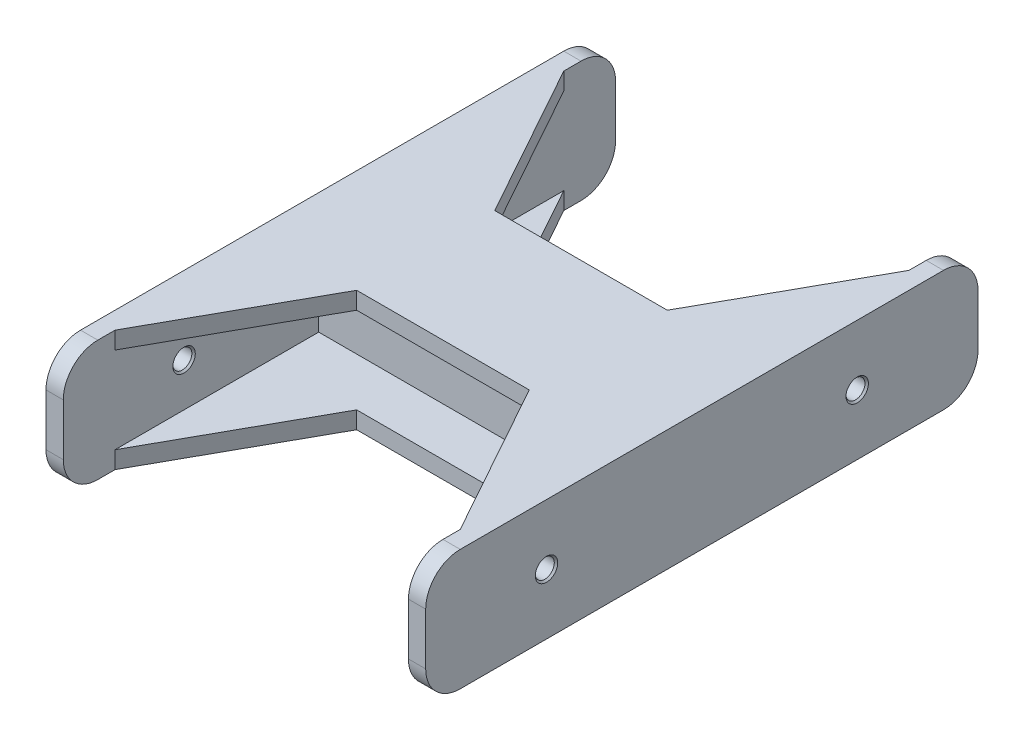
SolidWorks part; units mm, degrees
ref_plane "前视基准面" through (0, 0, 0) normal (0, 0, 1) x (1, 0, 0)
ref_plane "上视基准面" through (0, 0, 0) normal (0, 1, 0) x (1, 0, 0)
ref_plane "右视基准面" through (0, 0, 0) normal (1, 0, 0) x (0, 0, -1)
sketch "草图1" plane through (0, 0, 0) normal (1, 0, 0) x (0, 0, -1)
  line L1 (-80, 5) -> (80, 5)
  line L2 (-80, 5) -> (-80, -15)
  line L3 (-80, -15) -> (80, -15)
  line L4 (80, 5) -> (80, -15)
  dimension "D1" = 160
  dimension "D2" = 80
  dimension "D3" = 20
  dimension "D4" = 5
extrude "凸台-拉伸1" add sketch "草图1" along normal blind 5
sketch "草图3" plane through (5, 0, 0) normal (1, 0, 0) x (0, 0, -1)
  line L6 (-6, 5) -> (6, 5)
  line L7 (80, 5) -> (-80, 5) construction
  line L8 (6, 5) -> (6, -10)
  line L9 (6, -10) -> (20, -10)
  line L10 (20, -10) -> (20, -15)
  line L11 (-80, -15) -> (80, -15) construction
  line L12 (20, -15) -> (-20, -15)
  line L13 (-20, -15) -> (-20, -10)
  line L14 (-20, -10) -> (-6, -10)
  line L15 (-6, -10) -> (-6, 5)
  dimension "D1" = 6
  dimension "D2" = 6
  dimension "D3" = 5
  dimension "D4" = 5
  dimension "D5" = 20
  dimension "D6" = 20
extrude "凸台-拉伸3" add sketch "草图3" along normal blind 100
sketch "草图5" plane through (0, 0, 0) normal (-1, 0, 0) x (0, 0, 1)
  line L0 (-6, -10) -> (-6, 5) construction
  line L1 (6, 5) -> (-6, 5)
  line L2 (6, 5) -> (6, 20)
  line L3 (6, 20) -> (-6, 20)
  line L4 (-6, 5) -> (-6, 20)
  dimension "D1" = 15
extrude "凸台-拉伸4" add sketch "草图5" against normal blind 105
sketch "草图6" plane through (0, 0, 0) normal (-1, 0, 0) x (0, 0, 1)
  line L1 (6, 20) -> (80, 20)
  line L2 (6, 20) -> (6, 5)
  line L3 (6, 5) -> (80, 5)
  line L4 (80, 20) -> (80, 5)
  line L5 (-6, 20) -> (-80, 20)
  line L6 (-6, 20) -> (-6, 5)
  line L7 (-6, 5) -> (-80, 5)
  line L8 (-80, 20) -> (-80, 5)
extrude "凸台-拉伸5" add sketch "草图6" against normal blind 5
sketch "草图7" plane through (105, 0, 0) normal (1, 0, 0) x (0, 0, -1)
  line L1 (-80, -15) -> (80, -15)
  line L2 (-80, -15) -> (-80, 20)
  line L3 (-80, 20) -> (80, 20)
  line L4 (80, -15) -> (80, 20)
extrude "凸台-拉伸6" add sketch "草图7" along normal blind 5
sketch "草图8" plane through (0, -15, 0) normal (0, -1, 0) x (1, 0, 0)
  line L0 (80, 20) -> (105, 65)
  line L1 (105, 20) -> (5, 20) construction
  line L2 (105, 80) -> (105, 20) construction
  line L3 (105, 65) -> (105, 20)
  line L4 (105, 20) -> (80, 20)
  line L5 (0, 0) -> (50000, 0) construction
  line L6 (55, 20) -> (55, 50020) construction
  line L7 (105, -20) -> (80, -20)
  line L8 (105, -65) -> (105, -20)
  line L9 (80, -20) -> (105, -65)
  line L10 (5, 20) -> (30, 20)
  line L11 (5, 65) -> (5, 20)
  line L12 (30, 20) -> (5, 65)
  line L13 (30, -20) -> (5, -65)
  line L14 (5, -65) -> (5, -20)
  line L15 (5, -20) -> (30, -20)
  point P13 (55, 20)
  dimension "D1" = 45
  dimension "D2" = 25
extrude "凸台-拉伸7" add sketch "草图8" against normal blind 5
sketch "草图9" plane through (110, 0, 0) normal (1, 0, 0) x (0, 0, -1)
  line L0 (0, 0) -> (0, -50000) construction
  line L1 (80, 20) -> (-80, 20) construction
  circle A0 centre (45, 2.5) radius 2.75
  circle A1 centre (-45, 2.5) radius 2.75
  dimension "D1" = 5.5
  dimension "D2" = 17.5
  dimension "D3" = 45
extrude "切除-拉伸1" cut sketch "草图9" against normal through all
chamfer "倒角1" distance 0.5 angle 45 8 edges at (5, 2.5, 42.25) (0, 2.5, 47.75) (105, 2.5, 47.75) (110, 2.5, 47.75) (5, 2.5, -47.75) (0, 2.5, -47.75) (105, 2.5, -42.25) (110, 2.5, -47.75)
fillet "圆角1" radius 10 4 edges at (107.5, -15, -80) (107.5, -15, 80) (2.5, -15, 80) (2.5, -15, -80)
sketch "草图10" plane through (0, 20, 0) normal (0, 1, 0) x (1, 0, 0)
  line L6 (5, 65) -> (5, 6)
  line L7 (5, 6) -> (105, 6)
  line L8 (105, 6) -> (105, 65)
  line L9 (105, 65) -> (80, 20)
  line L10 (80, 20) -> (30, 20)
  line L11 (30, 20) -> (5, 65)
  line L12 (5, 65) -> (5, 6)
  line L13 (5, 6) -> (105, 6)
  line L14 (105, 6) -> (105, 65)
  line L15 (105, 65) -> (80, 20)
  line L16 (80, 20) -> (30, 20)
  line L17 (30, 20) -> (5, 65)
  line L18 (5, -6) -> (5, -65)
  line L19 (5, -65) -> (30, -20)
  line L20 (30, -20) -> (80, -20)
  line L21 (80, -20) -> (105, -65)
  line L22 (105, -65) -> (105, -6)
  line L23 (105, -6) -> (5, -6)
  line L24 (5, -6) -> (5, -65)
  line L25 (5, -65) -> (30, -20)
  line L26 (30, -20) -> (80, -20)
  line L27 (80, -20) -> (105, -65)
  line L28 (105, -65) -> (105, -6)
  line L29 (105, -6) -> (5, -6)
  dimension "D1" = 0
  dimension "D2" = 0
extrude "凸台-拉伸8" add sketch "草图10" against normal blind 5
fillet "圆角2" radius 10 4 edges at (107.5, 20, 80) (107.5, 20, -80) (2.5, 20, 80) (2.5, 20, -80)
